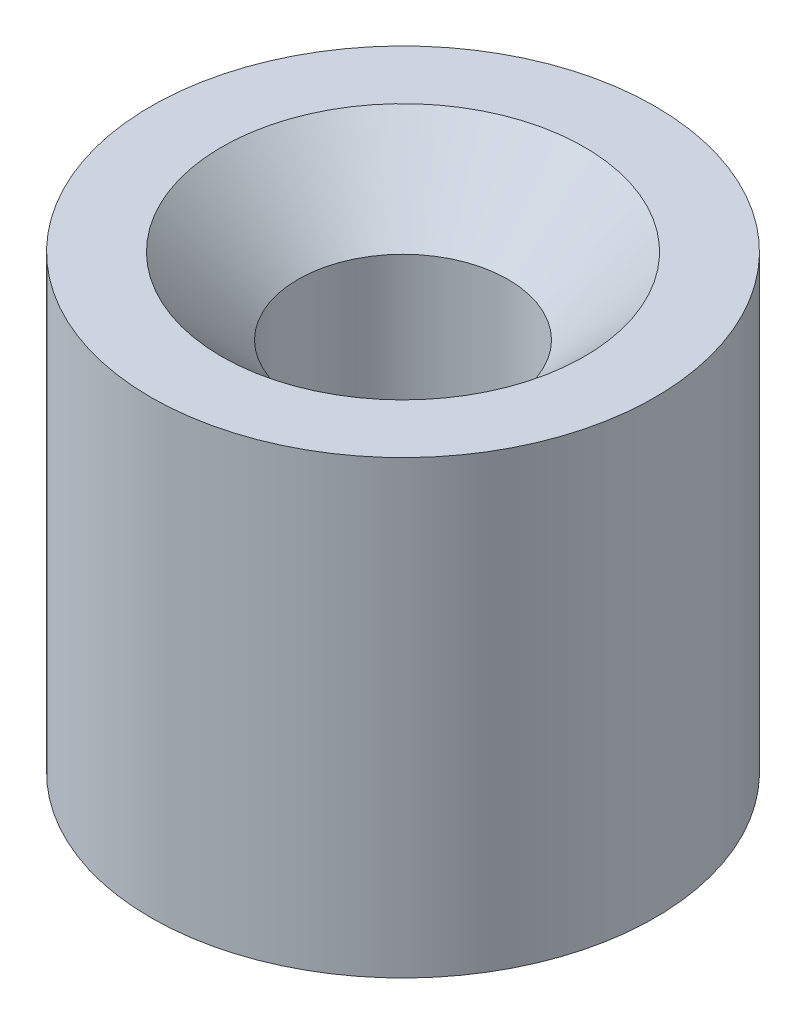
SolidWorks part; units mm, degrees
ref_plane "Front Plane" through (0, 0, 0) normal (0, 0, 1) x (1, 0, 0)
ref_plane "Top Plane" through (0, 0, 0) normal (0, 1, 0) x (1, 0, 0)
ref_plane "Right Plane" through (0, 0, 0) normal (1, 0, 0) x (0, 0, -1)
sketch "Sketch1" plane through (0, 0, 0) normal (0, 1, 0) x (1, 0, 0)
  circle A0 centre (0, 0) radius 2.75
  circle A1 centre (0, 0) radius 6.6
  dimension "D1" = 5.5
  dimension "D2" = 13.2
extrude "Boss-Extrude1" add sketch "Sketch1" along normal blind 11.8 contours A1 A0
chamfer "Chamfer1" distance 2 angle 45 2 edges at (0, 0, 2.75) (0, 11.8, 2.75)
